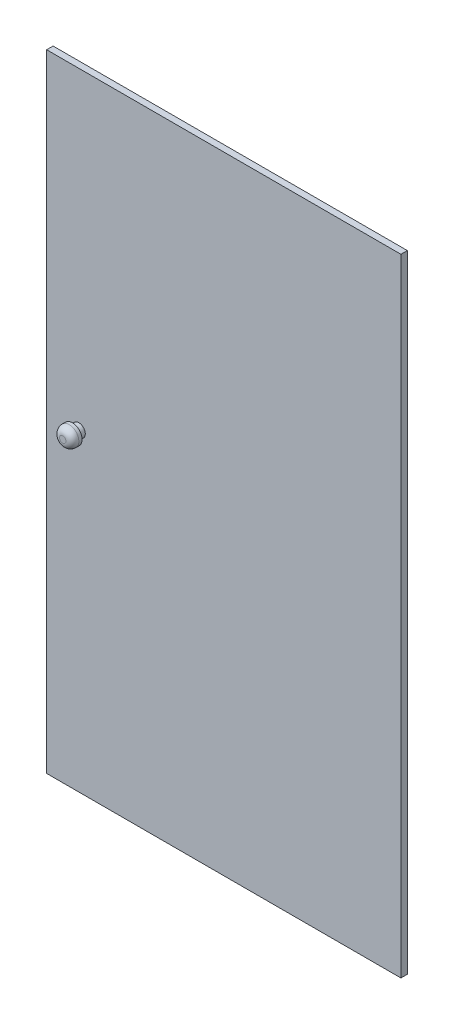
SolidWorks part; units mm, degrees
ref_plane "Front Plane" through (0, 0, 0) normal (0, 0, 1) x (1, 0, 0)
ref_plane "Top Plane" through (0, 0, 0) normal (0, 1, 0) x (1, 0, 0)
ref_plane "Right Plane" through (0, 0, 0) normal (1, 0, 0) x (0, 0, -1)
sketch "Sketch2" plane through (0, 0, 0) normal (0, 0, 1) x (1, 0, 0)
  line L1 (275, -486.5) -> (-275, -486.5)
  line L2 (275, -486.5) -> (275, 486.5)
  line L3 (275, 486.5) -> (-275, 486.5)
  line L4 (-275, -486.5) -> (-275, 486.5)
  line L5 (275, -486.5) -> (-275, 486.5) construction
  line L6 (275, 486.5) -> (-275, -486.5) construction
  point P0 (0, 0)
extrude "Boss-Extrude1" add sketch "Sketch2" along normal blind 10
sketch "Sketch3" plane through (0, 0, 10) normal (0, 0, 1) x (1, 0, 0)
  circle A0 centre (-225, 0) radius 10
extrude "Boss-Extrude2" add sketch "Sketch3" along normal blind 10
sketch "Sketch4" plane through (0, 0, 20) normal (0, 0, 1) x (1, 0, 0)
  circle A0 centre (-225, 0) radius 15
extrude "Boss-Extrude3" add sketch "Sketch4" along normal blind 15
fillet "Fillet1" radius 10 1 edges at (-210, 0, 35)
